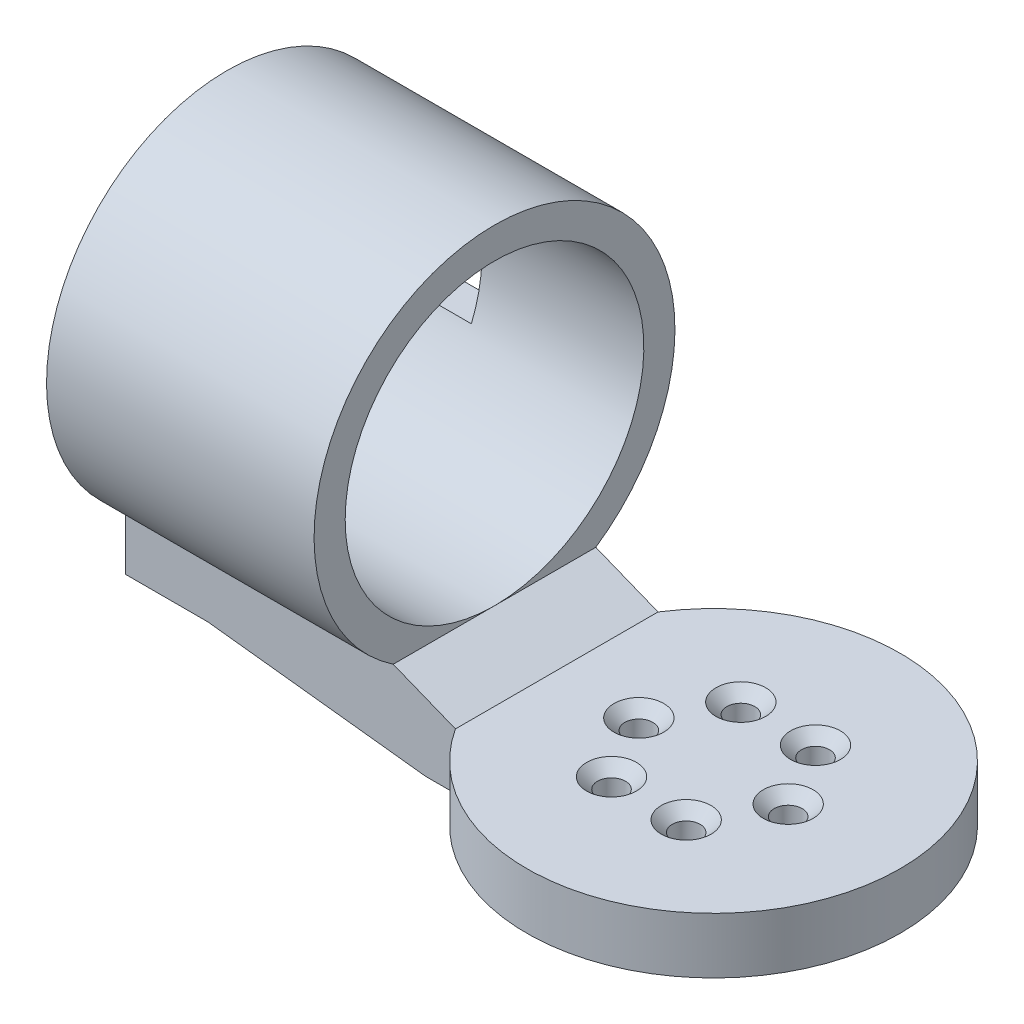
SolidWorks part; units mm, degrees
ref_plane "Front Plane" through (0, 0, 0) normal (0, 0, 1) x (1, 0, 0)
ref_plane "Top Plane" through (0, 0, 0) normal (0, 1, 0) x (1, 0, 0)
ref_plane "Right Plane" through (0, 0, 0) normal (1, 0, 0) x (0, 0, -1)
sketch "Sketch1" plane through (0, 0, 0) normal (0, 1, 0) x (1, 0, 0)
  line L0 (-21.2616, 0) -> (18.5116, 0) construction
  line L1 (-25.1984, -16.28) -> (-72.1984, -16.28)
  line L3 (-25.1984, 16.28) -> (-72.1984, 16.28)
  line L4 (-72.1984, -16.28) -> (-72.1984, 16.28)
  arc A0 (-25.1984, -16.28) -> (-25.1984, 16.28) centre (0, 0) ccw
  dimension "D1" = 60
  dimension "D2" = 32.56
  dimension "D3" = 47
extrude "Boss-Extrude1" add sketch "Sketch1" along normal blind 5
sketch "Sketch8" plane through (0, 5, 0) normal (0, 1, 0) x (1, 0, 0)
  line L0 (6, 10.3923) -> (-6, -10.3923) construction
  line L2 (6, -10.3923) -> (-6, 10.3923) construction
  line L5 (0, 0) -> (0, 12) construction
  circle A0 centre (0, 0) radius 12 construction
  point P4 (-12, 0)
  point P6 (12, 0)
  point P9 (6, 10.3923)
  point P10 (-6, -10.3923)
  point P13 (6, -10.3923)
  point P14 (-6, 10.3923)
  dimension "D1" = 24
  dimension "D2" = 30
  dimension "D3" = 30
hole_wizard "CSK for M4 Flat Head Machine Screw2" positions "Sketch8" profile "Sketch9" countersink size "M4" standard "ANSI Metric" end condition through all
sketch "Sketch9" plane through (-6, 5, -10.3923) normal (1, 0, 0) x (0, 0, 1)
  line L0 (0, 0) -> (0, 5)
  line L1 (0, 5) -> (2.25, 5)
  line L2 (2.25, 5) -> (2.25, 1.75)
  line L3 (2.25, 1.75) -> (4, 0)
  line L5 (4, 0) -> (0, 0)
  line L6 (-2.25, 1.75) -> (-4, 0) construction
  line L11 (0, -6.35) -> (0, 107.95) construction
  dimension "Thru Hole Dia." = 4.5
  dimension "Thru Hole Depth" = 5
  dimension "Near C'Sink Dia." = 8
  dimension "Near C'Sink Angle" = 90
sketch "Sketch11" plane through (-72.1984, 0, 0) normal (-1, 0, 0) x (0, 0, 1)
  line L0 (-16.28, 5) -> (16.28, 5) construction
  circle A0 centre (0, 33) radius 24
  circle A1 centre (0, 33) radius 29
  dimension "D1" = 48
  dimension "D2" = 28
  dimension "D3" = 5
extrude "Boss-Extrude2" add sketch "Sketch11" against normal blind 37
sketch "Sketch12" plane through (-72.1984, 0, 0) normal (-1, 0, 0) x (0, 0, 1)
  line L5 (-16.28, 0) -> (16.28, 0)
  line L6 (16.28, 0) -> (16.28, 5)
  line L7 (16.28, 5) -> (7.5498, 5)
  line L8 (-7.5498, 5) -> (-16.28, 5)
  line L9 (-16.28, 5) -> (-16.28, 0)
  line L10 (-16.28, 0) -> (16.28, 0)
  line L11 (16.28, 0) -> (16.28, 5)
  line L12 (16.28, 5) -> (7.5498, 5)
  line L13 (-7.5498, 5) -> (-16.28, 5)
  line L14 (-16.28, 5) -> (-16.28, 0)
  arc A1 (7.5498, 5) -> (-7.5498, 5) centre (0, 33) ccw
  arc A2 (7.5498, 5) -> (-7.5498, 5) centre (0, 33) ccw
  dimension "D1" = 0
extrude "Boss-Extrude3" add sketch "Sketch12" along normal blind 6
sketch "Sketch13" plane through (-78.1984, 0, 0) normal (-1, 0, 0) x (0, 0, 1)
  line L0 (0, 33) -> (0, 52.25) construction
  line L1 (0, 33) -> (11.5849, 48.3737) construction
  line L2 (0, 33) -> (-19.25, 33) construction
  line L3 (0, 33) -> (-15.3737, 44.5849) construction
  line L4 (0, 33) -> (15.3737, 21.4151) construction
  line L5 (0, 33) -> (-11.5849, 17.6263) construction
  circle A0 centre (0, 33) radius 19.25 construction
  arc A1 (7.5498, 5) -> (-7.5498, 5) centre (0, 33) ccw construction
  point P5 (11.5849, 48.3737)
  point P7 (15.3737, 21.4151)
  point P9 (-15.3737, 44.5849)
  point P10 (-11.5849, 17.6263)
  dimension "D1" = 38.5
  dimension "D2" = 37
  dimension "D3" = 37
hole_wizard "CSK for M3 Flat Head Machine Screw1" positions "Sketch13" profile "Sketch14" countersink size "M3" standard "ANSI Metric" end condition through all
sketch "Sketch14" plane through (-78.1984, 17.6263, -11.5849) normal (0, 1, 0) x (0, 0, 1)
  line L0 (0, 0) -> (0, 108.1984)
  line L1 (0, 108.1984) -> (1.7, 108.1984)
  line L2 (1.7, 108.1984) -> (1.7, 1.35)
  line L3 (1.7, 1.35) -> (3.05, 0)
  line L5 (3.05, 0) -> (0, 0)
  line L6 (-1.7, 1.35) -> (-3.05, 0) construction
  line L11 (0, -6.35) -> (0, 107.95) construction
  dimension "Thru Hole Dia." = 3.4
  dimension "Thru Hole Depth" = 108.1984
  dimension "Near C'Sink Dia." = 6.1
  dimension "Near C'Sink Angle" = 90
ref_plane "Plane1" through (0, 0, -29) normal (0, 0, -1) x (-1, 0, 0)
sketch "Sketch15" plane through (0, 0, -29) normal (0, 0, -1) x (-1, 0, 0)
  line L0 (35.1984, 33.5) -> (78.1984, 33.5) construction
  line L1 (35.1984, 62) -> (35.1984, 5) construction
  line L2 (78.1984, 5) -> (78.1984, 62) construction
  line L4 (68.1984, 24.1) -> (61.1984, 24.1)
  line L5 (68.1984, 24.1) -> (68.1984, 40.1)
  line L6 (68.1984, 40.1) -> (61.1984, 40.1)
  line L7 (61.1984, 24.1) -> (61.1984, 40.1)
  line L8 (68.1984, 24.1) -> (61.1984, 40.1) construction
  line L9 (68.1984, 40.1) -> (61.1984, 24.1) construction
  point P6 (64.6984, 32.1)
  dimension "D1" = 16
  dimension "D2" = 7
  dimension "D3" = 26
  dimension "D4" = 1.4
extrude "Cut-Extrude1" cut sketch "Sketch15" against normal up to next
sketch "Sketch17" plane through (0, 5, 0) normal (0, 1, 0) x (1, 0, 0)
  line L0 (0, 0) -> (0, 8.85) construction
  line L1 (7.6643, 4.425) -> (0, 0) construction
  line L2 (-7.6643, 4.425) -> (0, 0) construction
  line L3 (0, -8.85) -> (0, 0) construction
  circle A0 centre (0, 0) radius 8.85 construction
  circle A2 centre (-7.6643, 4.425) radius 2.9
  circle A3 centre (7.6643, 4.425) radius 2.9
  circle A4 centre (0, -8.85) radius 2.9
  dimension "D1" = 17.7
  dimension "D2" = 5.8
  dimension "D3" = 60
  dimension "D4" = 120
  dimension "D5" = 120
extrude "Cut-Extrude2" cut sketch "Sketch17" along normal blind 1 from surface at -5 starting at face at (-12, 0, 2.25)
chamfer "Chamfer1" distance 0.8 angle 45 3 edges at (-7.6643, 0, -1.525) (0, 0, 11.75) (7.6643, 0, -1.525)
ref_plane "Plane2" through (30, 0, 0) normal (1, 0, 0) x (0, 0, -1)
sketch "Sketch19" plane through (-35.1984, 0, 0) normal (1, 0, 0) x (0, 0, -1)
  line L0 (16.28, 9.0008) -> (16.28, 5)
  line L1 (7.5498, 5) -> (-7.5498, 5) construction
  line L2 (0, 42.2841) -> (0, -6.202) construction
  line L3 (16.28, 5) -> (7.5498, 5)
  line L4 (-16.28, 9.0008) -> (-16.28, 5)
  line L5 (-16.28, 5) -> (-7.5498, 5)
  arc A0 (7.5498, 5) -> (-7.5498, 5) centre (0, 33) ccw construction
  arc A1 (7.5498, 5) -> (16.28, 9.0008) centre (0, 33) ccw
  arc A2 (-7.5498, 5) -> (-16.28, 9.0008) centre (0, 33) cw
  arc M3 (7.5498, 5) -> (-7.5498, 5) centre (0, 33) ccw
  dimension "D1" = 32.56
extrude "Boss-Extrude4" add sketch "Sketch19" against normal up to surface (43 mm away) contours L4 L5 M3 | L3 L0 M3 up to face at (-78.1984, 48.3737, 14.6349)
sketch "Sketch20" plane through (0, 0, 0) normal (0, 0, 1) x (1, 0, 0)
  line L0 (-35.1984, 9.0008) -> (-25.1984, 5)
  line L1 (-25.1984, 5) -> (-35.1984, 5)
  line L2 (-35.1984, 5) -> (-35.1984, 9.0008)
extrude "Boss-Extrude5" add sketch "Sketch20" along normal mid plane 32.56
sketch "Sketch21" plane through (0, 0, 0) normal (0, -1, 0) x (1, 0, 0)
  circle A0 centre (0, 0) radius 30
  arc A1 (-25.1984, -16.28) -> (-25.1984, 16.28) centre (0, 0) ccw construction
  circle A2 centre (0, 0) radius 25
  dimension "D1" = 5
extrude "Boss-Extrude6" add sketch "Sketch21" along normal blind 4
sketch "Sketch22" plane through (0, 0, 16.28) normal (0, 0, 1) x (1, 0, 0)
  line L1 (-78.1984, 0) -> (-25.1984, 0) construction
  line L2 (-65, 0) -> (-25.1984, 0)
  line L3 (-25.1984, 0) -> (-25, -4)
  line L7 (-30, 0) -> (-30, -4) construction
  line L8 (-30, -4) -> (30, -4) construction
  line L9 (-30, -4) -> (-25, -4)
  line L10 (-30, -4) -> (-65, 0)
  dimension "D1" = 40
  dimension "D2" = 5
extrude "Boss-Extrude7" add sketch "Sketch22" against normal up to surface (32.56 mm away) up to face at (-48.3984, 4.6003, -16.28)
